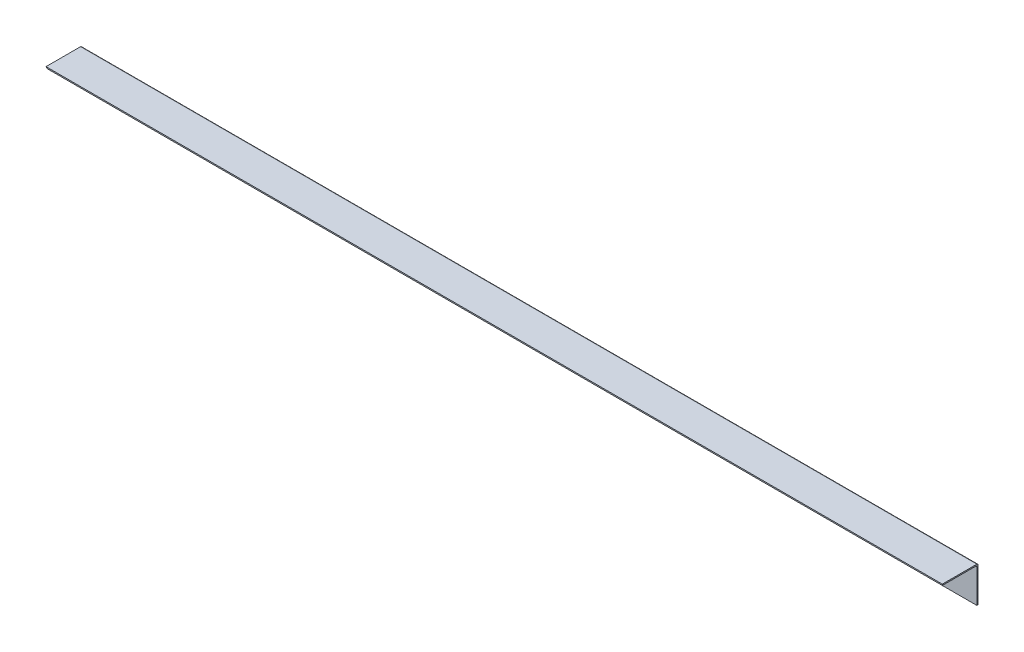
SolidWorks part; units mm, degrees
ref_plane "Front Plane" through (0, 0, 0) normal (0, 0, 1) x (1, 0, 0)
ref_plane "Top Plane" through (0, 0, 0) normal (0, 1, 0) x (1, 0, 0)
ref_plane "Right Plane" through (0, 0, 0) normal (1, 0, 0) x (0, 0, -1)
sketch "Sketch1" plane through (0, 0, 0) normal (1, 0, 0) x (0, 0, -1)
  line L0 (0, 0) -> (88, 0)
  line L1 (88, 0) -> (88, -88)
  line L2 (0, -3) -> (85, -3)
  line L3 (85, -3) -> (85, -88)
  line L4 (85, -88) -> (88, -88)
  line L5 (0, 0) -> (0, -3)
  dimension "D1" = 88
  dimension "D2" = 88
  dimension "D3" = 3
extrude "Boss-Extrude1" add sketch "Sketch1" along normal blind 2210
fillet "Fillet1" radius 3 2 edges at (1105, -3, -85) (1105, 0, -88)
sketch "Sketch3" plane through (0, 0, -88) normal (0, 0, -1) x (-1, 0, 0)
  line L0 (0, 0) -> (-88, -88)
  line L1 (-2210, -88) -> (0, -88) construction
  line L2 (-88, -88) -> (0, -88)
  line L3 (0, -88) -> (0, 0)
  dimension "D1" = 45
extrude "Cut-Extrude2" cut sketch "Sketch3" against normal blind 88
equation "\"equal_angleBar_FR_3mm_length\"= 2210"
equation "\"D1@Boss-Extrude1\"=\"equal_angleBar_FR_3mm_length\""
